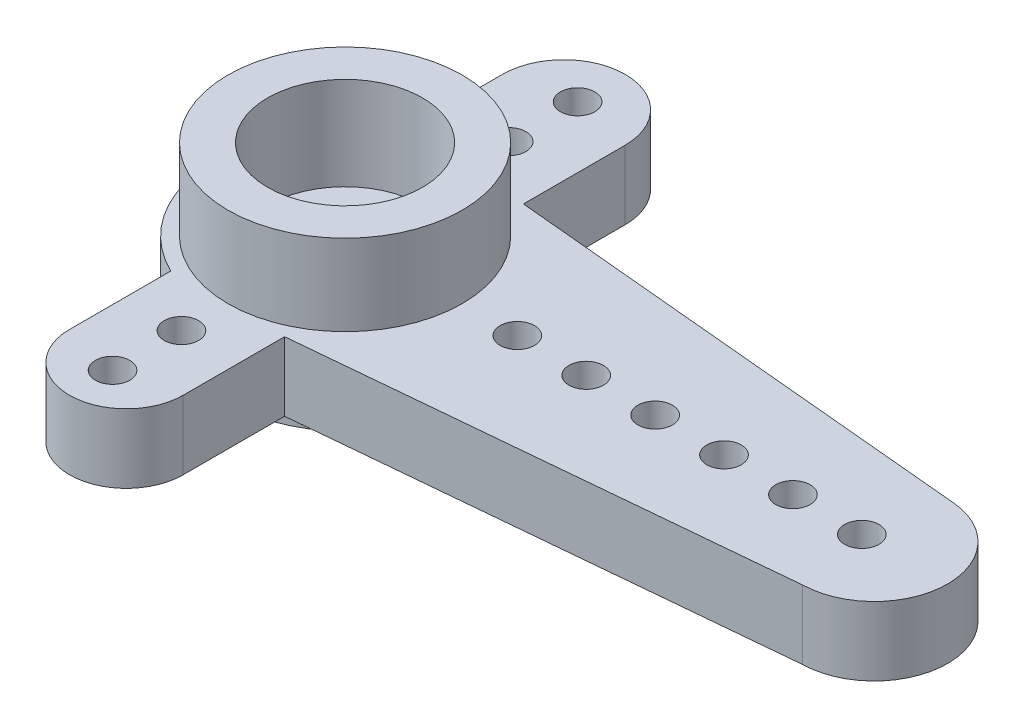
SolidWorks part; units mm, degrees
ref_plane "前视基准面" through (0, 0, 0) normal (0, 0, 1) x (1, 0, 0)
ref_plane "上视基准面" through (0, 0, 0) normal (0, 1, 0) x (1, 0, 0)
ref_plane "右视基准面" through (0, 0, 0) normal (1, 0, 0) x (0, 0, -1)
sketch "草图1" plane through (0, 0, 0) normal (0, 1, 0) x (1, 0, 0)
  circle A0 centre (0, 0) radius 2.25
  circle A1 centre (0, 0) radius 3.4
extrude "凸台-拉伸1" add sketch "草图1" along normal blind 4.85
sketch "草图2" plane through (0, 0, 0) normal (0, 1, 0) x (1, 0, 0)
  line L0 (-15, 0) -> (15, 0) construction
  line L1 (0, 6.75) -> (0, -6.75) construction
  line L16 (1.781, 3.3959) -> (1.781, 6.35)
  line L17 (-1.781, 6.35) -> (-1.781, 3.3421)
  line L20 (-1.6518, -3.4079) -> (-1.6518, -6.35)
  line L21 (1.6518, -6.35) -> (1.6518, -3.4079)
  line L22 (1.6518, -3.4079) -> (15.4101, -2.1303)
  line L23 (15.5576, 2.1217) -> (1.781, 3.3959)
  circle A0 centre (0, 0) radius 2.25 construction
  circle A1 centre (0, 0) radius 2.25
  circle A2 centre (0, -6.75) radius 0.5
  arc A3 (-1.781, 3.3421) -> (-1.6518, -3.4079) centre (0, 0) ccw
  circle A6 centre (0, 0) radius 3.4 construction
  arc A8 (1.781, 6.35) -> (-1.781, 6.35) centre (0, 6.35) ccw
  arc A10 (-1.6518, -6.35) -> (1.6518, -6.35) centre (0, -6.35) ccw
  arc A11 (15.4101, -2.1303) -> (15.5576, 2.1217) centre (15.3605, 0) ccw
  circle A12 centre (0, -4.75) radius 0.5
  circle A14 centre (15, 0) radius 0.5
  circle A16 centre (13, 0) radius 0.5
  circle A18 centre (11, 0) radius 0.5
  circle A20 centre (9, 0) radius 0.5
  circle A22 centre (7, 0) radius 0.5
  circle A24 centre (5, 0) radius 0.5
  circle A26 centre (0, 6.75) radius 0.5
  circle A28 centre (0, 4.75) radius 0.5
  dimension "D9" = 1
  dimension "D7" = 15.3605
  dimension "D1" = 2
  dimension "D2" = 2
  dimension "D3" = 2
  dimension "D4" = 2
  dimension "D5" = 2
  dimension "D6" = 15
  dimension "D8" = 13.5
  dimension "D15" = 2
  dimension "D16" = 2
extrude "凸台-拉伸2" add sketch "草图2" along normal blind 2 from offset 0.5
sketch "草图3" plane through (0, 0, 0) normal (0, 1, 0) x (1, 0, 0)
  circle A0 centre (0, 0) radius 1.15
  circle A1 centre (0, 0) radius 2.25 construction
  circle A2 centre (0, 0) radius 2.25
  dimension "D1" = 2.3
extrude "凸台-拉伸3" add sketch "草图3" along normal blind 0.9 from offset 1.25
